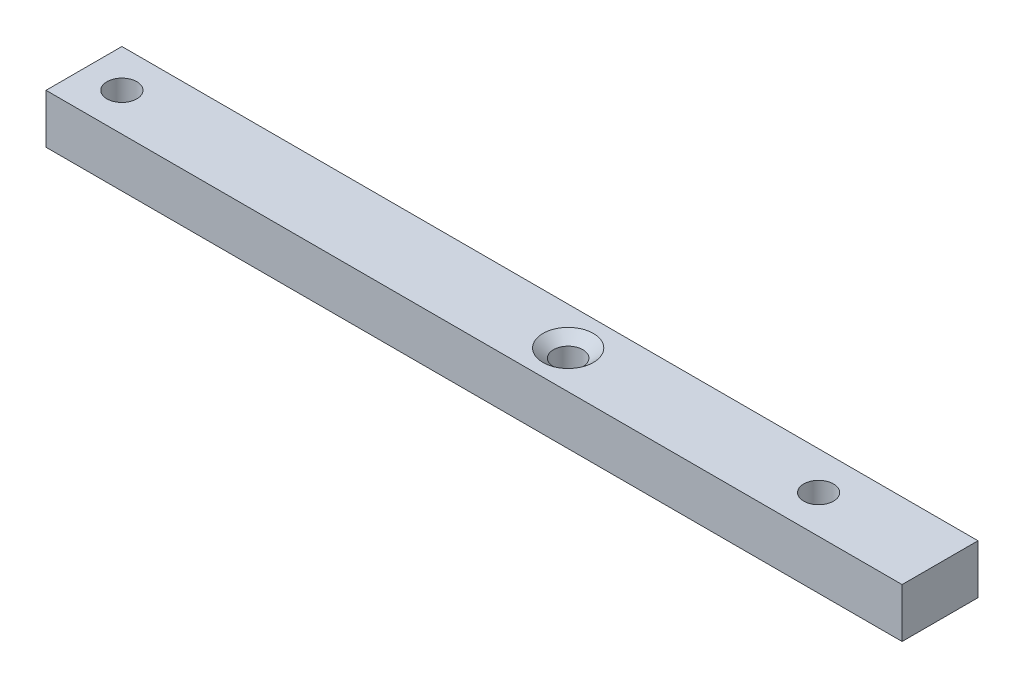
SolidWorks part; units mm, degrees
ref_plane "Front Plane" through (0, 0, 0) normal (0, 0, 1) x (1, 0, 0)
ref_plane "Top Plane" through (0, 0, 0) normal (0, 1, 0) x (1, 0, 0)
ref_plane "Right Plane" through (0, 0, 0) normal (1, 0, 0) x (0, 0, -1)
sketch "Sketch1" plane through (0, 0, 0) normal (0, 1, 0) x (1, 0, 0)
  line L1 (-64.4962, 10.7494) -> (78.7598, 10.7494)
  line L2 (-64.4962, 10.7494) -> (-64.4962, -1.9506)
  line L3 (-64.4962, -1.9506) -> (78.7598, -1.9506)
  line L4 (78.7598, 10.7494) -> (78.7598, -1.9506)
  dimension "D1" = 143.256
  dimension "D2" = 12.7
extrude "Boss-Extrude1" add sketch "Sketch1" along normal blind 8.255
hole_wizard "CSK for #8 Flat Head Machine Screw (100)1" positions "Sketch2" profile "Sketch3" countersink size "#8" standard "ANSI Inch" end condition through all
sketch "Sketch2" plane through (0, 8.255, 0) normal (0, 1, 0) x (1, 0, 0)
  line L0 (78.7598, 10.7494) -> (-64.4962, 10.7494) construction
  line L1 (78.7598, -1.9506) -> (78.7598, 10.7494) construction
  point P0 (16.5298, 4.3994)
  dimension "D1" = 6.35
  dimension "D2" = 62.23
sketch "Sketch3" plane through (16.5298, 8.255, -4.3994) normal (1, 0, 0) x (0, 0, 1)
  line L0 (0, 0) -> (0, 8.255)
  line L1 (0, 8.255) -> (2.4574, 8.255)
  line L2 (2.4574, 8.255) -> (2.4574, 1.4759)
  line L3 (2.4574, 1.4759) -> (4.2164, 0)
  line L5 (4.2164, 0) -> (0, 0)
  line L6 (-2.4574, 1.4759) -> (-4.2164, 0) construction
  line L11 (0, -6.35) -> (0, 107.95) construction
  dimension "Thru Hole Dia." = 4.9149
  dimension "Thru Hole Depth" = 8.255
  dimension "Near C'Sink Dia." = 8.4328
  dimension "Near C'Sink Angle" = 100
sketch "Sketch4" plane through (0, 8.255, 0) normal (0, 1, 0) x (1, 0, 0)
  circle A0 centre (16.5298, 4.3994) radius 4.318
  dimension "D1" = 8.636
hole_wizard "Tap Drill for #2-56 Tap2" positions "Sketch8" profile "Sketch9" hole size "#2-56" standard "ANSI Inch"
sketch "Sketch8" plane through (0, 0, 0) normal (0, -1, 0) x (-1, 0, 0)
  line L0 (64.4962, -1.9506) -> (-78.7598, -1.9506) construction
  point P0 (50.0275, 2.7484)
  point P2 (40.5025, 2.7484)
  dimension "D1" = 4.699
  dimension "D2" = 4.699
  dimension "D3" = 9.525
sketch "Sketch9" plane through (-50.0275, 0, -2.7484) normal (1, 0, 0) x (0, 0, -1)
  line L0 (0, 0) -> (0, 6.8842)
  line L1 (0, 6.8842) -> (0.889, 6.35)
  line L2 (0.889, 6.35) -> (0.889, 0)
  line L5 (0.889, 0) -> (0, 0)
  line L10 (0, 6.8842) -> (-0.889, 6.35) construction
  line L11 (0, -6.35) -> (0, 107.95) construction
  dimension "Hole Dia." = 1.778
  dimension "Hole Depth" = 6.35
  dimension "Drill Angle" = 118
hole_wizard "Tap Drill for M6x1.0 Tap1" positions "Sketch10" profile "Sketch11" hole size "M6x1.0" standard "ANSI Metric" end condition through all
sketch "Sketch10" plane through (0, 8.255, 0) normal (0, 1, 0) x (1, 0, 0)
  line L0 (78.7598, -1.9506) -> (78.7598, 10.7494) construction
  line L1 (-64.4962, -1.9506) -> (78.7598, -1.9506) construction
  line L2 (-64.4962, 10.7494) -> (-64.4962, -1.9506) construction
  point P0 (58.4398, 4.3994)
  point P2 (-58.1462, 4.3994)
  dimension "D1" = 20.32
  dimension "D2" = 6.35
  dimension "D3" = 6.35
  dimension "D4" = 6.35
sketch "Sketch11" plane through (58.4398, 8.255, -4.3994) normal (1, 0, 0) x (0, 0, 1)
  line L0 (0, 0) -> (0, 8.255)
  line L1 (0, 8.255) -> (2.5, 8.255)
  line L2 (2.5, 8.255) -> (2.5, 0)
  line L5 (2.5, 0) -> (0, 0)
  line L11 (0, -6.35) -> (0, 107.95) construction
  dimension "Thru Hole Dia." = 5
  dimension "Thru Hole Depth" = 8.255
